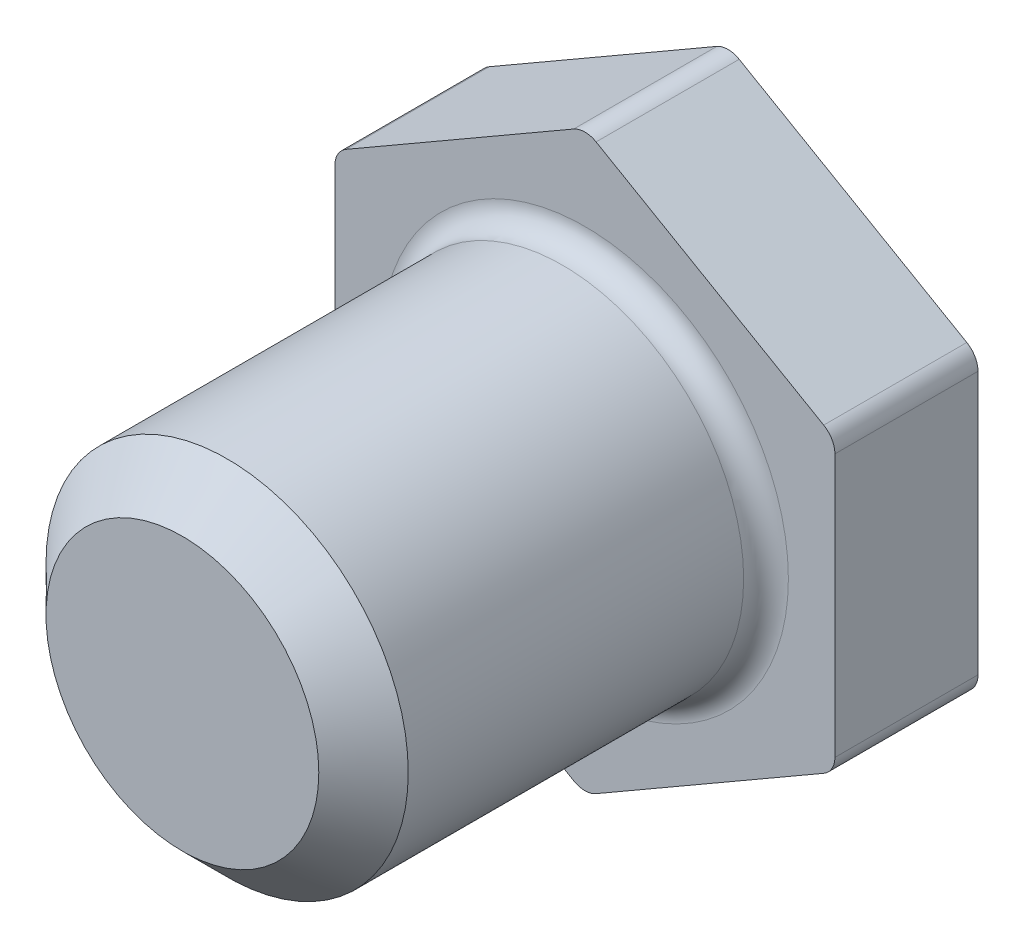
SolidWorks part; units mm, degrees
material "Anycubic PLA V3.0"
ref_plane "Front Plane" through (0, 0, 0) normal (0, 0, 1) x (1, 0, 0)
ref_plane "Top Plane" through (0, 0, 0) normal (0, 1, 0) x (1, 0, 0)
ref_plane "Right Plane" through (0, 0, 0) normal (1, 0, 0) x (0, 0, -1)
sketch "Sketch1" plane through (0, 0, 0) normal (0, 0, 1) x (1, 0, 0)
  line L0 (5.59, 3.2274) -> (0, 6.4548)
  line L7 (0, 6.4548) -> (-5.59, 3.2274)
  line L8 (-5.59, 3.2274) -> (-5.59, -3.2274)
  line L9 (-5.59, -3.2274) -> (0, -6.4548)
  line L10 (0, -6.4548) -> (5.59, -3.2274)
  line L11 (5.59, -3.2274) -> (5.59, 3.2274)
  line L12 (5.59, 3.2274) -> (0, 6.4548)
  line L13 (0, 6.4548) -> (-5.59, 3.2274)
  line L14 (-5.59, 3.2274) -> (-5.59, -3.2274)
  line L15 (-5.59, -3.2274) -> (0, -6.4548)
  line L16 (0, -6.4548) -> (5.59, -3.2274)
  line L17 (5.59, -3.2274) -> (5.59, 3.2274)
  circle A0 centre (0, 0) radius 6.4548 construction
  dimension "D1" = 11.18
  dimension "D2" = 11.18
extrude "Boss-Extrude1" add sketch "Sketch1" along normal blind 3.2 contours L0 L13 L14 L15 L16 L17
sketch "Sketch2" plane through (0, 0, 3.2) normal (0, 0, 1) x (1, 0, 0)
  circle A0 centre (0, 0) radius 4.05
  dimension "D1" = 8.1
extrude "Boss-Extrude2" add sketch "Sketch2" along normal blind 9
fillet "Fillet1" radius 0.5 7 edges at (4.05, 0, 3.2) (-5.59, 3.2274, 1.6) (-5.59, -3.2274, 1.6) (0, -6.4548, 1.6) (5.59, -3.2274, 1.6) (5.59, 3.2274, 1.6) (0, 6.4548, 1.6)
chamfer "Chamfer1" distance 1 angle 45 1 edges at (4.05, 0, 12.2)
